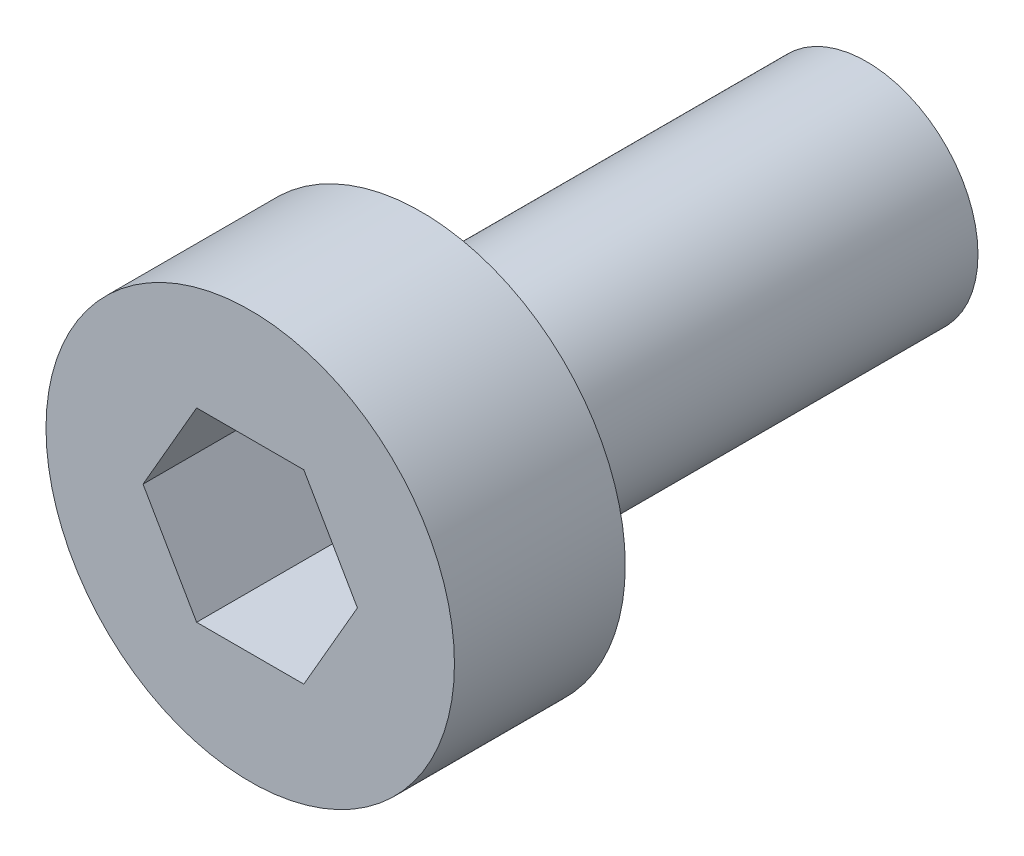
SolidWorks part; units mm, degrees
ref_plane "Plan de face" through (0, 0, 0) normal (0, 0, 1) x (1, 0, 0)
ref_plane "Plan de dessus" through (0, 0, 0) normal (0, 1, 0) x (1, 0, 0)
ref_plane "Plan de droite" through (0, 0, 0) normal (1, 0, 0) x (0, 0, -1)
sketch "Esquisse1" plane through (0, 0, 0) normal (0, 0, 1) x (1, 0, 0)
  circle A0 centre (0, 0) radius 1.5
  dimension "D1" = 3
extrude "Boss.-Extru.1" add sketch "Esquisse1" along normal blind 6
sketch "Esquisse2" plane through (0, 0, 6) normal (0, 0, 1) x (1, 0, 0)
  circle A0 centre (0, 0) radius 2.75
  dimension "D1" = 5.5
extrude "Boss.-Extru.2" add sketch "Esquisse2" along normal blind 2.3
sketch "Esquisse3" plane through (0, 0, 8.3) normal (0, 0, 1) x (1, 0, 0)
  line L1 (1.4434, 0) -> (0.7217, 1.25)
  line L2 (0.7217, 1.25) -> (-0.7217, 1.25)
  line L3 (-0.7217, 1.25) -> (-1.4434, 0)
  line L4 (-1.4434, 0) -> (-0.7217, -1.25)
  line L5 (-0.7217, -1.25) -> (0.7217, -1.25)
  line L6 (0.7217, -1.25) -> (1.4434, 0)
  circle A0 centre (0, 0) radius 1.25 construction
  dimension "D1" = 2.5
extrude "Enlèv. mat.-Extru.1" cut sketch "Esquisse3" against normal blind 2
